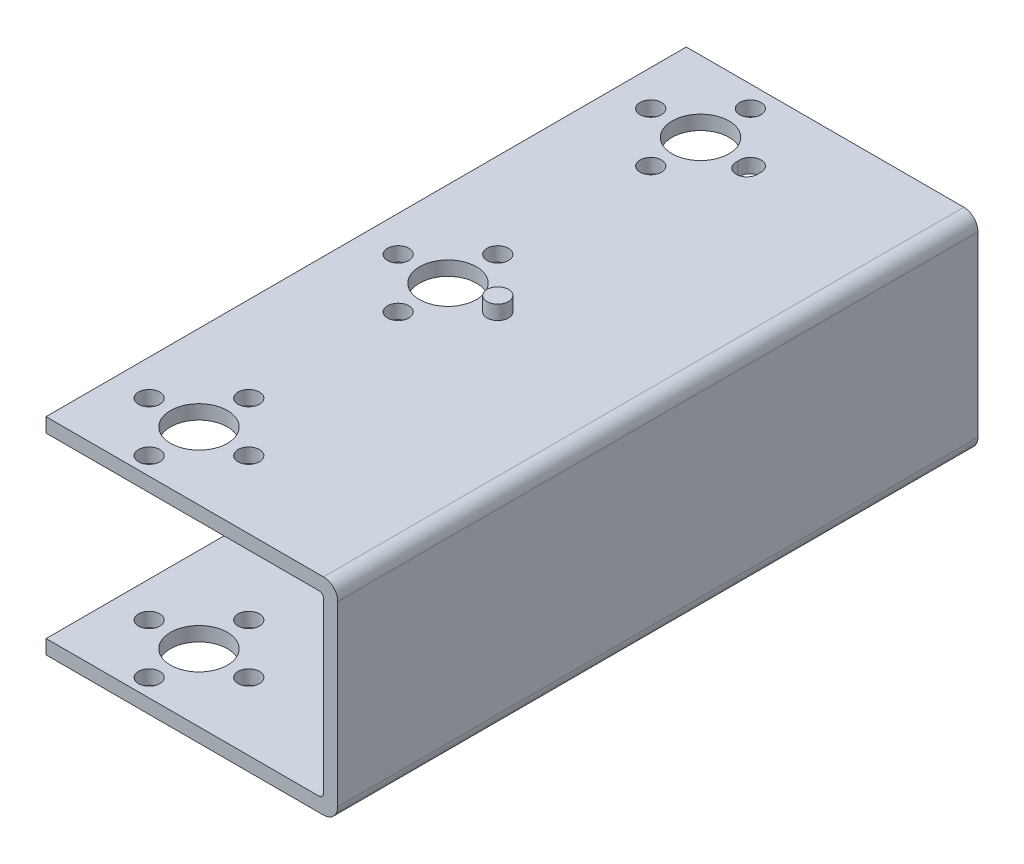
SolidWorks part; units mm, degrees
material "1060 Alloy"
ref_plane "Front Plane" through (0, 0, 0) normal (0, 0, 1) x (1, 0, 0)
ref_plane "Top Plane" through (0, 0, 0) normal (0, 1, 0) x (1, 0, 0)
ref_plane "Right Plane" through (0, 0, 0) normal (1, 0, 0) x (0, 0, -1)
sketch "Sketch3" plane through (0, 0, 0) normal (0, 0, 1) x (1, 0, 0)
  line L0 (-2, 0.0494) -> (-41, 0.0494)
  line L1 (-41, 0.0494) -> (-41, 2.0494)
  line L2 (-41, 2.0494) -> (-2.6183, 2.0494)
  line L4 (-0.0182, 27.0494) -> (-0.0182, 2.0494)
  line L5 (-2.0182, 29.0494) -> (-41.0182, 29.0494)
  line L6 (-41.0182, 29.0494) -> (-41.0182, 27.0494)
  line L7 (-41.0182, 27.0494) -> (-2.6183, 27.0494)
  line L8 (-2.6183, 2.6494) -> (-2.6183, 2.0494) construction
  line L9 (-2.0183, 26.4494) -> (-2.0183, 2.6494)
  line L10 (-2.6183, 2.6494) -> (-2.0183, 2.6494) construction
  arc A0 (-0.0182, 27.0494) -> (-2.0182, 29.0494) centre (-2.0182, 27.0494) ccw
  arc A1 (-0.0182, 2.0494) -> (-2, 0.0494) centre (-2.0183, 2.0494) cw
  arc A2 (-2.6183, 27.0494) -> (-2.0183, 26.4494) centre (-2.6183, 26.4494) cw
  arc A3 (-2.6183, 2.0494) -> (-2.0183, 2.6494) centre (-2.6183, 2.6494) ccw
  dimension "D1" = 0.6
  dimension "D2" = 0.6
  dimension "D3" = 2
  dimension "D4" = 0.6
extrude "Boss-Extrude1" add sketch "Sketch3" along normal blind 90
ref_plane "Plane1" through (0, 29.0494, 0) normal (0, 1, 0) x (1, 0, 0)
sketch "Sketch4" plane through (0, 29.0494, 0) normal (0, 1, 0) x (1, 0, 0)
  line L0 (-41.0182, 0) -> (-29.0182, 0)
  line L1 (-2.0182, 0) -> (-41.0182, 0) construction
  line L2 (-29.0182, 0) -> (-29.0182, -10)
  line L3 (-29.0182, -10) -> (-36.0182, -10) construction
  circle A0 centre (-29.0182, -10) radius 4
  circle A1 centre (-36.0182, -10) radius 1.5
  circle A2 centre (-29.0182, -3) radius 1.5
  circle A3 centre (-22.0182, -10) radius 1.5
  circle A4 centre (-29.0182, -17) radius 1.5
  point P18 (-29.0182, -10)
  dimension "D3" = 4
  dimension "D1" = 12
  dimension "D2" = 10
extrude "Cut-Extrude1" cut sketch "Sketch4" against normal blind 31
sketch "Sketch6" plane through (0, 29.0494, 0) normal (0, 1, 0) x (1, 0, 0)
  line L0 (-29.0182, -10) -> (-29.0182, -45.4989) construction
  line L1 (-29.0182, -45.4989) -> (-29.0182, -80.4989) construction
  line L2 (-36.0182, -10) -> (-36.0182, -45.4989) construction
  line L3 (-36.0182, -45.4989) -> (-36.0182, -80.4989) construction
  circle A0 centre (-29.0182, -45.4989) radius 4
  circle A1 centre (-29.0182, -80.4989) radius 4
  circle A2 centre (-36.0182, -45.4989) radius 1.5
  circle A3 centre (-36.0182, -80.4989) radius 1.5
  circle A4 centre (5.9818, -52.4989) radius 1.5
  circle A5 centre (-29.0182, -52.4989) radius 1.5
  circle A6 centre (-22.0182, -10.4989) radius 1.5
  circle A7 centre (-22.0182, -45.4989) radius 1.5
  circle A8 centre (-64.0182, -38.4989) radius 1.5
  circle A9 centre (-29.0182, -38.4989) radius 1.5
  circle A10 centre (-29.0182, -73.4989) radius 1.5
  circle A11 centre (-22.0182, -80.4989) radius 1.5
  circle A12 centre (-29.0182, -87.4989) radius 1.5
  point P27 (-29.0182, -45.4989)
  point P34 (-29.0182, -80.4989)
  dimension "D1" = 3
  dimension "D2" = 3
  dimension "D3" = 4
  dimension "D4" = 4
extrude "Cut-Extrude2" cut sketch "Sketch6" against normal blind 31
sketch "Sketch7" plane through (0, 29.0494, 0) normal (0, 1, 0) x (1, 0, 0)
  circle A0 centre (-22.0182, -45.4989) radius 1.5
extrude "Boss-Extrude2" add sketch "Sketch7" along normal blind 2 separate body
